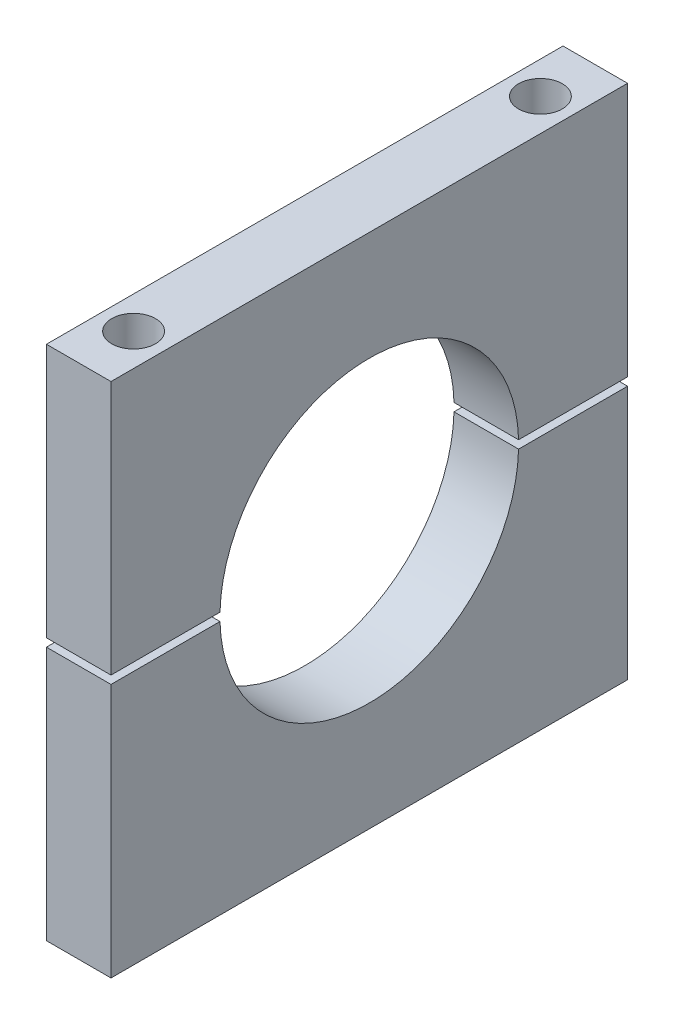
SolidWorks part; units mm, degrees
ref_plane "Front Plane" through (0, 0, 0) normal (0, 0, 1) x (1, 0, 0)
ref_plane "Top Plane" through (0, 0, 0) normal (0, 1, 0) x (1, 0, 0)
ref_plane "Right Plane" through (0, 0, 0) normal (1, 0, 0) x (0, 0, -1)
sketch "Sketch1" plane through (0, 0, 0) normal (1, 0, 0) x (0, 0, -1)
  line L0 (-25.4, 0.3969) -> (25.4, 0.3969)
  line L1 (-25.4, -25.4) -> (25.4, -25.4)
  line L2 (-25.4, -25.4) -> (-25.4, 25.4)
  line L3 (-25.4, 25.4) -> (25.4, 25.4)
  line L4 (25.4, -25.4) -> (25.4, 25.4)
  line L5 (-25.4, -25.4) -> (25.4, 25.4) construction
  line L6 (-25.4, 25.4) -> (25.4, -25.4) construction
  line L7 (-25.4, 0.3969) -> (-25.4, -0.3969)
  line L8 (25.4, 0.3969) -> (25.4, -0.3969)
  line L9 (-25.4, -0.3969) -> (25.4, -0.3969)
  line L10 (-25.4, 0.3969) -> (25.4, -0.3969) construction
  line L11 (25.4, 0.3969) -> (-25.4, -0.3969) construction
  circle A0 centre (0, 0) radius 14.2875 construction
  circle A1 centre (0, 0) radius 14.6875
  point P0 (0, 0)
  dimension "D1" = 28.575
  dimension "D2" = 0.4
  dimension "D3" = 50.8
  dimension "D4" = 0.7937
extrude "Boss-Extrude1" add sketch "Sketch1" along normal mid plane 6.35 contours A1 L0 L4 L3 L2 | A1 L9 L2 L1 L4
sketch "Sketch3" plane through (0, 25.4, 0) normal (0, 1, 0) x (1, 0, 0)
  line L0 (3.175, -25.4) -> (-3.175, -25.4) construction
  line L1 (3.175, 25.4) -> (-3.175, 25.4) construction
  point P0 (0, 20.0025)
  point P1 (0, -20.0025)
  dimension "D1" = 5.3975
  dimension "D2" = 5.3975
hole_wizard "#18 (0.1695) Diameter Hole2" positions "3DSketch1" profile "Sketch4" hole size "#18" standard "ANSI Inch" end condition up to next
sketch3d "3DSketch1"
  point P0 (0, 25.4, 20.0025)
  point P3 (0, 25.4, -20.0025)
sketch "Sketch4" plane through (0, 25.4, 20.0025) normal (1, 0, 0) x (0, 0, 1)
  line L0 (0, 0) -> (0, 25.0031)
  line L1 (0, 25.0031) -> (2.1526, 25.0031)
  line L2 (2.1526, 25.0031) -> (2.1526, 0)
  line L5 (2.1526, 0) -> (0, 0)
  line L11 (0, -6.35) -> (0, 107.95) construction
  dimension "Thru Hole Dia." = 4.3053
  dimension "Thru Hole Depth" = 25.0031
hole_wizard "#29 (0.136) Diameter Hole1" positions "3DSketch2" profile "Sketch5" hole size "#29" standard "ANSI Inch" end condition up to next
sketch3d "3DSketch2"
  point P0 (0, 25.4, 20.0025)
  point P3 (0, 25.4, -20.0025)
sketch "Sketch5" plane through (0, 25.4, 20.0025) normal (1, 0, 0) x (0, 0, 1)
  line L0 (0, 0) -> (0, 50.8)
  line L1 (0, 50.8) -> (1.7272, 50.8)
  line L2 (1.7272, 50.8) -> (1.7272, 0)
  line L5 (1.7272, 0) -> (0, 0)
  line L11 (0, -6.35) -> (0, 107.95) construction
  dimension "Thru Hole Dia." = 3.4544
  dimension "Thru Hole Depth" = 50.8
